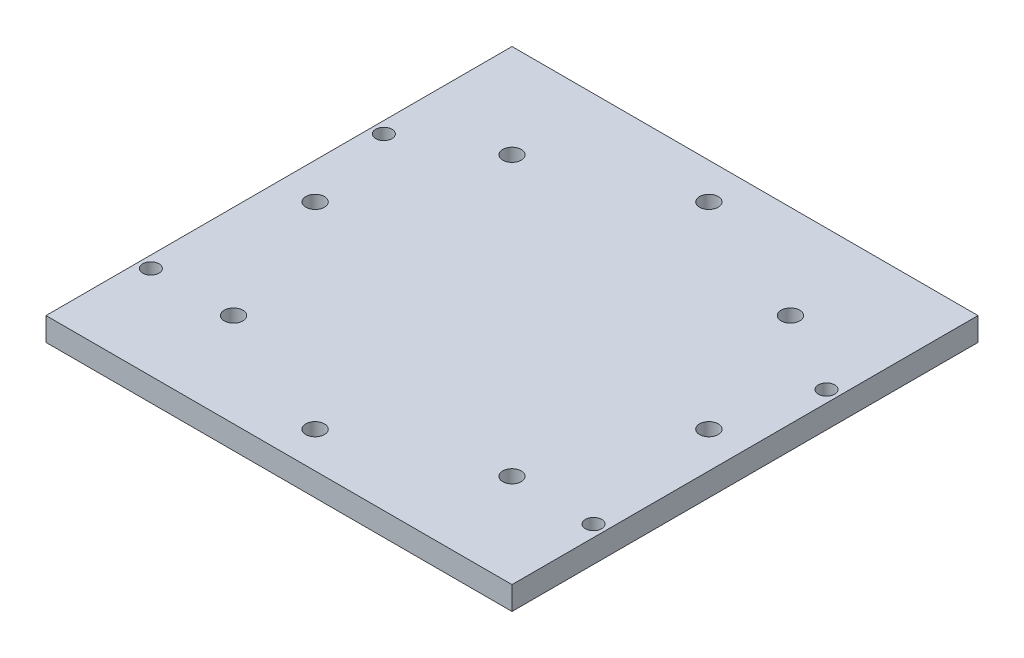
SolidWorks part; units mm, degrees
ref_plane "Front Plane" through (0, 0, 0) normal (0, 0, 1) x (1, 0, 0)
ref_plane "Top Plane" through (0, 0, 0) normal (0, 1, 0) x (1, 0, 0)
ref_plane "Right Plane" through (0, 0, 0) normal (1, 0, 0) x (0, 0, -1)
sketch "Sketch2" plane through (0, 0, 0) normal (0, 1, 0) x (1, 0, 0)
  line L0 (0, 0) -> (100, 100) construction
  line L1 (0, 0) -> (100, 0)
  line L2 (0, 0) -> (0, 100)
  line L3 (0, 100) -> (100, 100)
  line L4 (100, 0) -> (100, 100)
  line L5 (2.5, 90) -> (2.5, 0) construction
  line L6 (7.75, 50) -> (50, 50) construction
  line L7 (50, 50) -> (50, 92.25) construction
  line L8 (2.5, 70) -> (2.5, 20) construction
  circle A0 centre (50, 50) radius 45 construction
  circle A1 centre (50, 50) radius 39.5 construction
  circle A2 centre (50, 50) radius 42.25 construction
  circle A3 centre (50, 92.25) radius 2
  circle A4 centre (79.8753, 79.8753) radius 2
  circle A5 centre (92.25, 50) radius 2
  circle A6 centre (79.8753, 20.1247) radius 2
  circle A7 centre (50, 7.75) radius 2
  circle A8 centre (20.1247, 20.1247) radius 2
  circle A9 centre (7.75, 50) radius 2
  circle A10 centre (20.1247, 79.8753) radius 2
  circle A11 centre (2.5, 20) radius 1.75
  circle A12 centre (2.5, 70) radius 1.75
  circle A13 centre (97.5, 20) radius 1.75
  circle A14 centre (97.5, 70) radius 1.75
  point P27 (50, 50)
  point P36 (0, 0)
  point P37 (7.75, 50)
  point P38 (7.75, 5)
  point P39 (7.75, 50)
  point P40 (7.75, 95)
  point P41 (0, 0)
  point P42 (7.75, 0)
  point P43 (7.75, 50)
  dimension "D1" = 90
  dimension "D2" = 50
  dimension "D4" = 5.5
  dimension "D5" = 2.75
  dimension "D6" = 4
  dimension "D9" = 50
  dimension "D10" = 3.5
  dimension "D3" = 50
  dimension "D8" = 90
  dimension "D11" = 20
  dimension "D12" = 2.5
  dimension "D7" = 8
extrude "Boss-Extrude1" add sketch "Sketch2" along normal blind 5
